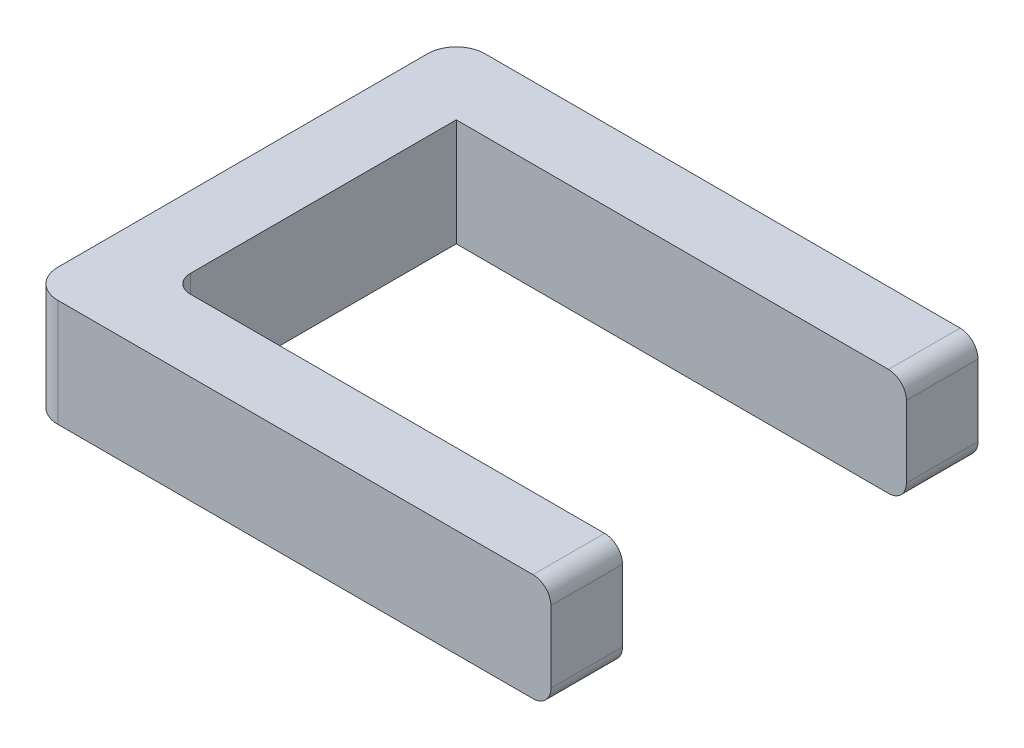
SolidWorks part; units mm, degrees
ref_plane "Front Plane" through (0, 0, 0) normal (0, 0, 1) x (1, 0, 0)
ref_plane "Top Plane" through (0, 0, 0) normal (0, 1, 0) x (1, 0, 0)
ref_plane "Right Plane" through (0, 0, 0) normal (1, 0, 0) x (0, 0, -1)
sketch "Sketch4" plane through (0, 0, 0) normal (0, 1, 0) x (1, 0, 0)
  line L0 (-25.4, -25.4) -> (159.6762, -25.4)
  line L1 (0, 0) -> (159.6762, 0)
  line L2 (0, 0) -> (0, 50.3562)
  line L4 (159.6762, 0) -> (159.6762, -25.4)
  line L5 (-25.4, 50.3562) -> (0, 50.3562)
  line L7 (-25.4, -25.4) -> (-25.4, 50.3562)
  line L10 (0, 125.9828) -> (209.2965, 125.9828) construction
  line L11 (-25.4, 151.3828) -> (234.6965, 151.3828) construction
  line L12 (0, 0) -> (209.2965, 0) construction
  line L13 (-25.4, -25.4) -> (234.6965, -25.4) construction
  line L14 (209.2965, 0) -> (209.2965, 125.9828) construction
  line L15 (234.6965, -25.4) -> (234.6965, 151.3828) construction
  line L16 (0, 0) -> (0, 125.9828) construction
  line L17 (-25.4, -25.4) -> (-25.4, 151.3828) construction
extrude "Extrude4" add sketch "Sketch4" against normal blind 38.1
fillet "Fillet1" radius 6.35 3 edges at (159.6762, -38.1, 12.7) (159.6762, 0, 12.7) (0, -19.05, 0)
fillet "Fillet2" radius 10.16 1 edges at (-25.4, -19.05, 25.4)
mirror "Mirror1" about plane through (-25.4, -38.1, -50.3562) normal (0, 0, -1) of "Extrude4", "Fillet2"
fillet "Fillet4" radius 6.35 2 edges at (159.6762, 0, -113.4124) (159.6762, -38.1, -113.4124)
ref_plane "Plane1" through (0, 0, -53.5312) normal (0, 0, 1) x (1, 0, 0)
sketch "Sketch5" plane through (0, 0, -53.5312) normal (0, 0, 1) x (1, 0, 0)
  line L0 (159.6762, -19.05) -> (138.2557, -19.05) construction
  line L1 (159.6762, -31.75) -> (159.6762, -6.35) construction
  circle A0 centre (138.2557, -19.05) radius 12.8216
